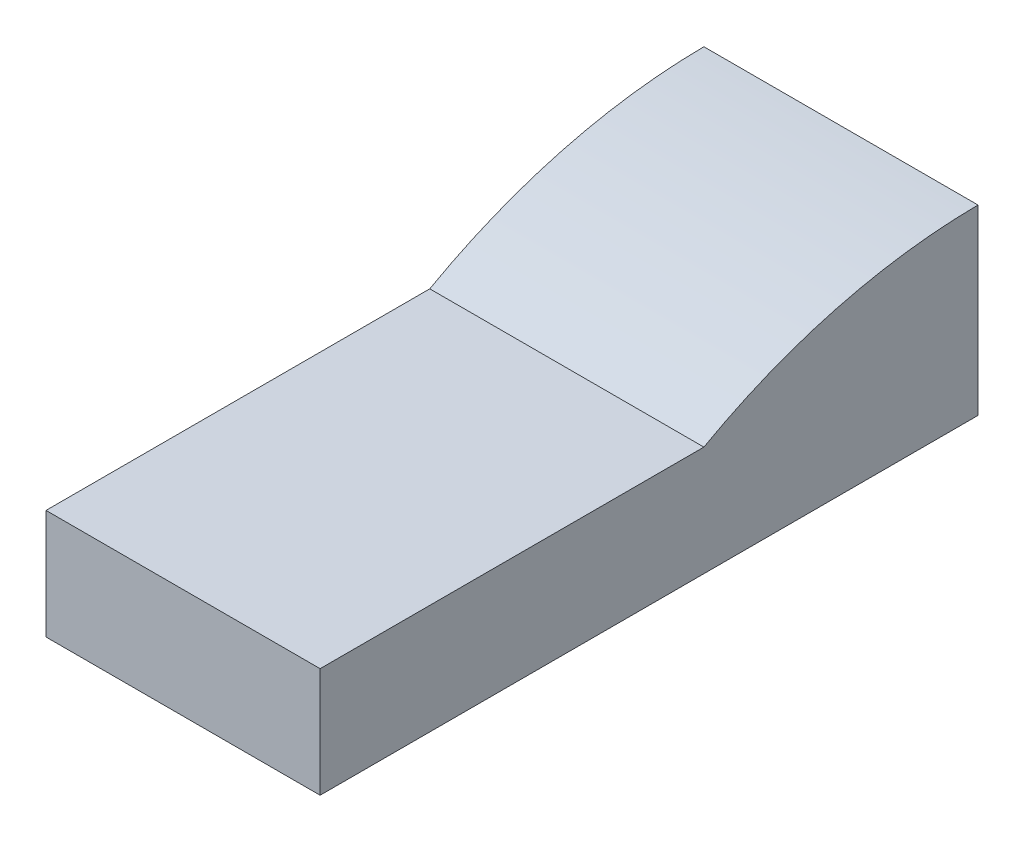
SolidWorks part; units mm, degrees
ref_plane "Front Plane" through (0, 0, 0) normal (0, 0, 1) x (1, 0, 0)
ref_plane "Top Plane" through (0, 0, 0) normal (0, 1, 0) x (1, 0, 0)
ref_plane "Right Plane" through (0, 0, 0) normal (1, 0, 0) x (0, 0, -1)
sketch "Sketch1" plane through (0, 0, 0) normal (1, 0, 0) x (0, 0, -1)
  line L0 (12.7, 5.2689) -> (12.7, 1.905)
  line L1 (12.7, -3.175) -> (-17.78, -3.175)
  line L2 (12.7, -3.175) -> (12.7, 1.905)
  line L3 (0, 1.905) -> (-17.78, 1.905)
  line L4 (-17.78, -3.175) -> (-17.78, 1.905)
  line L7 (12.7, 5.2689) -> (12.7, 1.905)
  arc A0 (0, 1.905) -> (12.7, 5.2689) centre (12.8969, -21.1301) cw
  point P0 (0, 0)
  point P9 (0, 0)
  dimension "D1" = 5.08
  dimension "D2" = 30.48
extrude "Boss-Extrude1" add sketch "Sketch1" along normal blind 12.7 contours A0 L3 L4 L1 L2 L0
